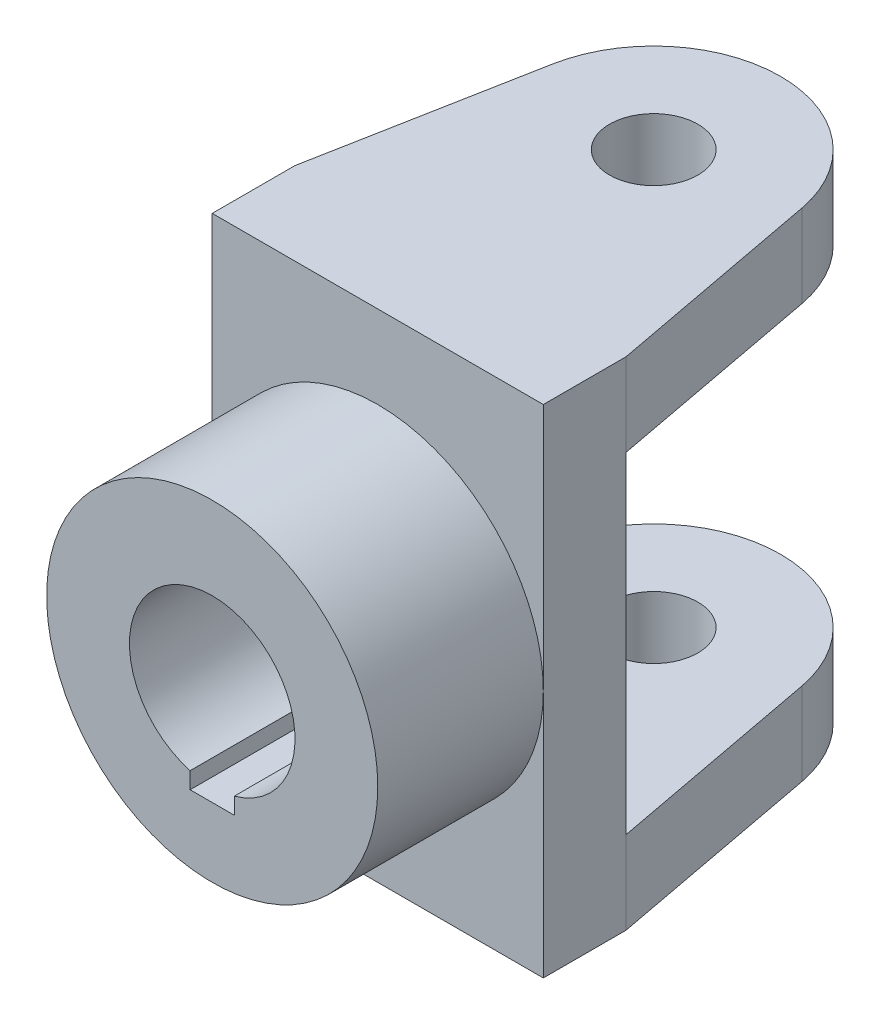
SolidWorks part; units mm, degrees
ref_plane "Front Plane" through (0, 0, 0) normal (0, 0, 1) x (1, 0, 0)
ref_plane "Top Plane" through (0, 0, 0) normal (0, 1, 0) x (1, 0, 0)
ref_plane "Right Plane" through (0, 0, 0) normal (1, 0, 0) x (0, 0, -1)
sketch "Sketch2" plane through (0, 0, 0) normal (0, 1, 0) x (1, 0, 0)
  line L0 (30, -35) -> (22.6022, 4.259)
  line L2 (-30, -35) -> (-30, -50)
  line L3 (-30, -50) -> (30, -50)
  line L4 (30, -35) -> (30, -50)
  line L5 (-30, -35) -> (-22.6022, 4.259)
  line L6 (0, 0) -> (0, -8)
  arc A0 (22.6022, 4.259) -> (-22.6022, 4.259) centre (0, 0) ccw
  circle A1 centre (0, 0) radius 8
  point P11 (0, 0)
  point P13 (0, 0)
  dimension "D3" = 46
  dimension "D4" = 16
  dimension "D1" = 60
  dimension "D2" = 15
extrude "Boss-Extrude1" add sketch "Sketch2" against normal blind 90 contours L0 A0 L5 L2 L3 L4 A1
sketch "Sketch3" plane through (0, 0, 50) normal (0, 0, 1) x (1, 0, 0)
  line L0 (30, 0) -> (-30, -90) construction
  line L1 (-30, 0) -> (30, -90) construction
  line L2 (30, -90) -> (30, 0) construction
  circle A0 centre (0, -45) radius 30
extrude "Boss-Extrude2" add sketch "Sketch3" along normal blind 30
sketch "Sketch4" plane through (0, 0, 80) normal (0, 0, 1) x (1, 0, 0)
  line L0 (0, -45) -> (0, -60) construction
  line L1 (-4, -62.4568) -> (4, -62.4568)
  line L2 (4, -62.4568) -> (4, -59.4568)
  line L3 (-4, -62.4568) -> (-4, -59.4568)
  arc A0 (4, -59.4568) -> (-4, -59.4568) centre (0, -45) ccw
  point P8 (0, -62.4568)
  dimension "D1" = 30
  dimension "D2" = 8
  dimension "D3" = 3
extrude "Cut-Extrude1" cut sketch "Sketch4" against normal through all
sketch "Sketch5" plane through (30, 0, 0) normal (1, 0, 0) x (0, 0, -1)
  line L0 (-35, -90) -> (-35, 0) construction
  line L1 (-35, -15) -> (23, -15)
  line L2 (-35, -15) -> (-35, -75)
  line L3 (-35, -75) -> (23, -75)
  line L4 (23, -15) -> (23, -75)
  line L5 (23, -90) -> (23, -62.4568) construction
  line L6 (-35, 0) -> (-50, 0) construction
  line L7 (-35, -90) -> (-50, -90) construction
  dimension "D1" = 15
  dimension "D2" = 15
extrude "Cut-Extrude2" cut sketch "Sketch5" against normal through all
